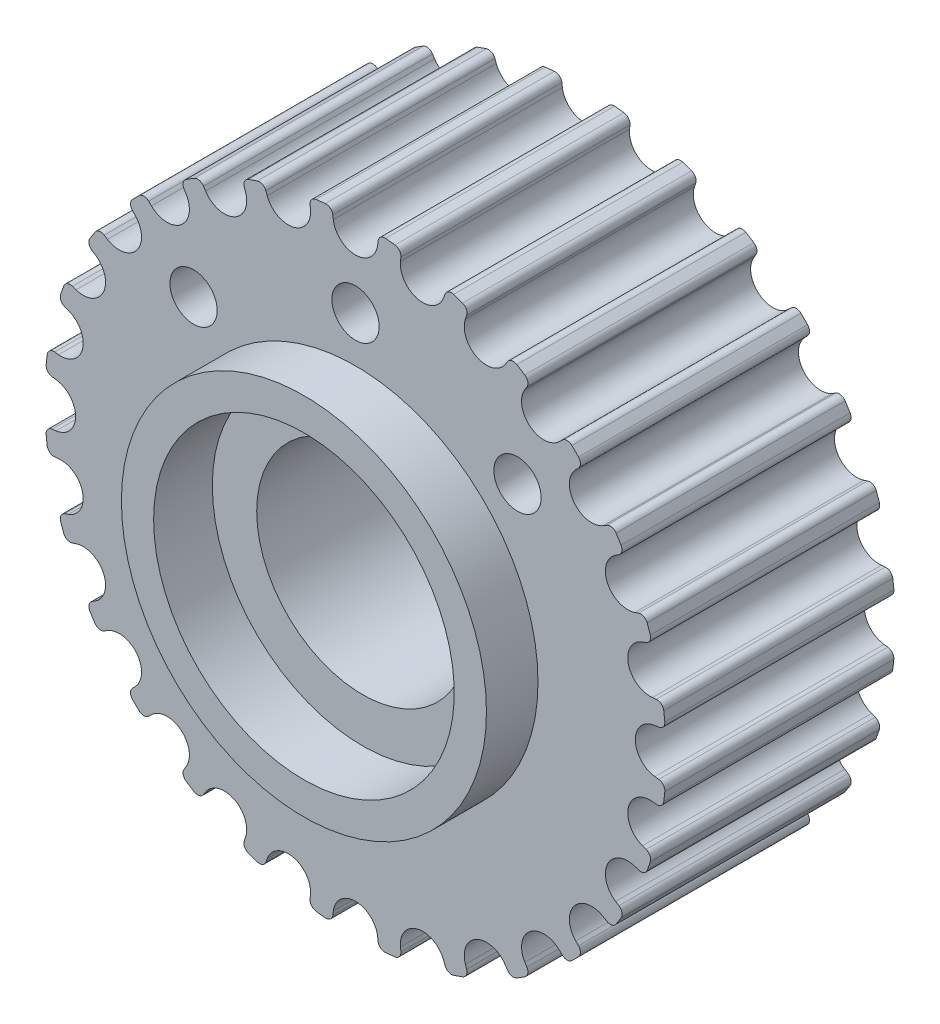
SolidWorks part; units mm, degrees
ref_plane "前视基准面" through (0, 0, 0) normal (0, 0, 1) x (1, 0, 0)
ref_plane "上视基准面" through (0, 0, 0) normal (0, 1, 0) x (1, 0, 0)
ref_plane "右视基准面" through (0, 0, 0) normal (1, 0, 0) x (0, 0, -1)
sketch "草图2" plane through (0, 0, 0) normal (0, 0, 1) x (1, 0, 0)
  line L36 (1.3319, 20.7804) -> (1.2989, 20.5118)
  line L37 (-1.7978, 20.5118) -> (-1.8308, 20.7804)
  line L38 (-3.4222, 20.6011) -> (-3.3946, 20.3319)
  line L39 (-6.4137, 19.6428) -> (-6.5056, 19.8973)
  line L40 (-8.0172, 19.3684) -> (-7.9303, 19.1121)
  line L41 (-10.7204, 17.7684) -> (-10.8667, 17.9962)
  line L42 (-12.2227, 17.1441) -> (-12.081, 16.9135)
  line L43 (-14.5021, 14.9827) -> (-14.6954, 15.1722)
  line L44 (-15.8278, 14.0398) -> (-15.6383, 13.8465)
  line L45 (-17.5691, 11.4254) -> (-17.7997, 11.5671)
  line L46 (-18.6517, 10.2111) -> (-18.424, 10.0648)
  line L47 (-19.7676, 7.2748) -> (-20.024, 7.3616)
  line L48 (-20.5529, 5.85) -> (-20.2983, 5.7581)
  line L49 (-20.9874, 2.739) -> (-21.2567, 2.7666)
  line L50 (-21.436, 1.1752) -> (-21.1673, 1.1423)
  line L51 (-21.1673, -1.9545) -> (-21.436, -1.9875)
  line L52 (-21.2567, -3.5789) -> (-20.9874, -3.5512)
  line L53 (-20.2983, -6.5703) -> (-20.5529, -6.6623)
  line L54 (-20.024, -8.1739) -> (-19.7676, -8.087)
  line L55 (-18.424, -10.8771) -> (-18.6517, -11.0234)
  line L56 (-17.7997, -12.3793) -> (-17.5691, -12.2376)
  line L57 (-15.6383, -14.6588) -> (-15.8278, -14.8521)
  line L58 (-14.6954, -15.9845) -> (-14.5021, -15.795)
  line L59 (-12.081, -17.7258) -> (-12.2227, -17.9564)
  line L60 (-10.8667, -18.8084) -> (-10.7204, -18.5807)
  line L61 (-7.9303, -19.9243) -> (-8.0172, -20.1806)
  line L62 (-6.5056, -20.7096) -> (-6.4137, -20.455)
  line L63 (-3.3946, -21.1441) -> (-3.4222, -21.4133)
  line L64 (-1.8308, -21.5926) -> (-1.7978, -21.324)
  line L65 (1.2989, -21.324) -> (1.3319, -21.5926)
  line L66 (2.9233, -21.4133) -> (2.8957, -21.1441)
  line L67 (5.9148, -20.455) -> (6.0067, -20.7096)
  line L68 (7.5183, -20.1806) -> (7.4314, -19.9243)
  line L69 (10.2215, -18.5807) -> (10.3678, -18.8084)
  line L70 (11.7238, -17.9564) -> (11.5821, -17.7258)
  line L71 (14.0032, -15.795) -> (14.1965, -15.9845)
  line L72 (15.3289, -14.8521) -> (15.1394, -14.6588)
  line L73 (17.0702, -12.2376) -> (17.3008, -12.3793)
  line L74 (18.1528, -11.0234) -> (17.9251, -10.8771)
  line L75 (19.2687, -8.087) -> (19.5251, -8.1739)
  line L76 (20.054, -6.6623) -> (19.7994, -6.5703)
  line L77 (20.4885, -3.5512) -> (20.7578, -3.5789)
  line L78 (20.9371, -1.9875) -> (20.6684, -1.9545)
  line L79 (20.6684, 1.1423) -> (20.9371, 1.1752)
  line L80 (20.7578, 2.7666) -> (20.4885, 2.739)
  line L81 (19.7994, 5.7581) -> (20.054, 5.85)
  line L82 (19.5251, 7.3616) -> (19.2687, 7.2748)
  line L83 (17.9251, 10.0648) -> (18.1528, 10.2111)
  line L84 (17.3008, 11.5671) -> (17.0702, 11.4254)
  line L85 (15.1394, 13.8465) -> (15.3289, 14.0398)
  line L86 (14.1965, 15.1722) -> (14.0032, 14.9827)
  line L87 (11.5821, 16.9135) -> (11.7238, 17.1441)
  line L88 (10.3678, 17.9962) -> (10.2215, 17.7684)
  line L89 (7.4314, 19.1121) -> (7.5183, 19.3684)
  line L90 (6.0067, 19.8973) -> (5.9148, 19.6428)
  line L91 (2.8957, 20.3319) -> (2.9233, 20.6011)
  circle A72 centre (-0.2458, -0.3677) radius 12 construction
  circle A73 centre (-0.2458, -0.3677) radius 10.5
  arc A74 (2.9233, 20.6011) -> (2.5067, 21.1262) centre (2.4458, 20.6501) ccw
  arc A75 (2.5067, 21.1262) -> (1.8549, 21.1996) centre (-0.2495, -0.4061) ccw
  arc A76 (1.8549, 21.1996) -> (1.3319, 20.7804) centre (1.8083, 20.7219) ccw
  arc A77 (-1.7978, 20.5118) -> (1.2989, 20.5118) centre (-0.2495, 20.7019) ccw
  arc A78 (-1.8308, 20.7804) -> (-2.3538, 21.1996) centre (-2.3072, 20.7219) ccw
  arc A79 (-2.3538, 21.1996) -> (-3.0056, 21.1262) centre (-0.2495, -0.4061) ccw
  arc A80 (-3.0056, 21.1262) -> (-3.4222, 20.6011) centre (-2.9447, 20.6501) ccw
  arc A81 (-6.4137, 19.6428) -> (-3.3946, 20.3319) centre (-4.9464, 20.1727) ccw
  arc A82 (-6.5056, 19.8973) -> (-7.1087, 20.1897) centre (-6.9571, 19.7343) ccw
  arc A83 (-7.1087, 20.1897) -> (-7.7279, 19.973) centre (-0.2495, -0.4061) ccw
  arc A84 (-7.7279, 19.973) -> (-8.0172, 19.3684) centre (-7.5626, 19.5224) ccw
  arc A85 (-10.7204, 17.7684) -> (-7.9303, 19.1121) centre (-9.4079, 18.6115) ccw
  arc A86 (-10.8667, 17.9962) -> (-11.5198, 18.147) centre (-11.2706, 17.7367) ccw
  arc A87 (-11.5198, 18.147) -> (-12.0752, 17.798) centre (-0.2495, -0.4061) ccw
  arc A88 (-12.0752, 17.798) -> (-12.2227, 17.1441) centre (-11.8137, 17.3954) ccw
  arc A89 (-14.5021, 14.9827) -> (-12.081, 16.9135) centre (-13.4101, 16.0968) ccw
  arc A90 (-14.6954, 15.1722) -> (-15.3656, 15.1739) centre (-15.0314, 14.8294) ccw
  arc A91 (-15.3656, 15.1739) -> (-15.8295, 14.7101) centre (-0.2495, -0.4061) ccw
  arc A92 (-15.8295, 14.7101) -> (-15.8278, 14.0398) centre (-15.485, 14.3758) ccw
  arc A93 (-17.5691, 11.4254) -> (-15.6383, 13.8465) centre (-16.7524, 12.7545) ccw
  arc A94 (-17.7997, 11.5671) -> (-18.4535, 11.4196) centre (-18.051, 11.1582) ccw
  arc A95 (-18.4535, 11.4196) -> (-18.8026, 10.8642) centre (-0.2495, -0.4061) ccw
  arc A96 (-18.8026, 10.8642) -> (-18.6517, 10.2111) centre (-18.3923, 10.615) ccw
  arc A97 (-19.7676, 7.2748) -> (-18.424, 10.0648) centre (-19.2671, 8.7523) ccw
  arc A98 (-20.024, 7.3616) -> (-20.6286, 7.0724) centre (-20.178, 6.907) ccw
  arc A99 (-20.6286, 7.0724) -> (-20.8453, 6.4532) centre (-0.2495, -0.4061) ccw
  arc A100 (-20.8453, 6.4532) -> (-20.5529, 5.85) centre (-20.3899, 6.3015) ccw
  arc A101 (-20.9874, 2.739) -> (-20.2983, 5.7581) centre (-20.8282, 4.2909) ccw
  arc A102 (-21.2567, 2.7666) -> (-21.7818, 2.3501) centre (-21.3057, 2.2891) ccw
  arc A103 (-21.7818, 2.3501) -> (-21.8552, 1.6982) centre (-0.2495, -0.4061) ccw
  arc A104 (-21.8552, 1.6982) -> (-21.436, 1.1752) centre (-21.3775, 1.6517) ccw
  arc A105 (-21.1673, -1.9545) -> (-21.1673, 1.1423) centre (-21.3575, -0.4061) ccw
  arc A106 (-21.436, -1.9875) -> (-21.8552, -2.5104) centre (-21.3775, -2.4639) ccw
  arc A107 (-21.8552, -2.5104) -> (-21.7818, -3.1623) centre (-0.2495, -0.4061) ccw
  arc A108 (-21.7818, -3.1623) -> (-21.2567, -3.5789) centre (-21.3057, -3.1014) ccw
  arc A109 (-20.2983, -6.5703) -> (-20.9874, -3.5512) centre (-20.8282, -5.1031) ccw
  arc A110 (-20.5529, -6.6623) -> (-20.8453, -7.2654) centre (-20.3899, -7.1137) ccw
  arc A111 (-20.8453, -7.2654) -> (-20.6286, -7.8846) centre (-0.2495, -0.4061) ccw
  arc A112 (-20.6286, -7.8846) -> (-20.024, -8.1739) centre (-20.178, -7.7192) ccw
  arc A113 (-18.424, -10.8771) -> (-19.7676, -8.087) centre (-19.2671, -9.5645) ccw
  arc A114 (-18.6517, -11.0234) -> (-18.8026, -11.6764) centre (-18.3923, -11.4272) ccw
  arc A115 (-18.8026, -11.6764) -> (-18.4535, -12.2319) centre (-0.2495, -0.4061) ccw
  arc A116 (-18.4535, -12.2319) -> (-17.7997, -12.3793) centre (-18.051, -11.9704) ccw
  arc A117 (-15.6383, -14.6588) -> (-17.5691, -12.2376) centre (-16.7524, -13.5667) ccw
  arc A118 (-15.8278, -14.8521) -> (-15.8295, -15.5223) centre (-15.485, -15.1881) ccw
  arc A119 (-15.8295, -15.5223) -> (-15.3656, -15.9862) centre (-0.2495, -0.4061) ccw
  arc A120 (-15.3656, -15.9862) -> (-14.6954, -15.9845) centre (-15.0314, -15.6417) ccw
  arc A121 (-12.081, -17.7258) -> (-14.5021, -15.795) centre (-13.4101, -16.909) ccw
  arc A122 (-12.2227, -17.9564) -> (-12.0752, -18.6102) centre (-11.8137, -18.2077) ccw
  arc A123 (-12.0752, -18.6102) -> (-11.5198, -18.9592) centre (-0.2495, -0.4061) ccw
  arc A124 (-11.5198, -18.9592) -> (-10.8667, -18.8084) centre (-11.2706, -18.549) ccw
  arc A125 (-7.9303, -19.9243) -> (-10.7204, -18.5807) centre (-9.4079, -19.4238) ccw
  arc A126 (-8.0172, -20.1806) -> (-7.7279, -20.7853) centre (-7.5626, -20.3347) ccw
  arc A127 (-7.7279, -20.7853) -> (-7.1087, -21.0019) centre (-0.2495, -0.4061) ccw
  arc A128 (-7.1087, -21.0019) -> (-6.5056, -20.7096) centre (-6.9571, -20.5465) ccw
  arc A129 (-3.3946, -21.1441) -> (-6.4137, -20.455) centre (-4.9464, -20.9849) ccw
  arc A130 (-3.4222, -21.4133) -> (-3.0056, -21.9384) centre (-2.9447, -21.4623) ccw
  arc A131 (-3.0056, -21.9384) -> (-2.3538, -22.0119) centre (-0.2495, -0.4061) ccw
  arc A132 (-2.3538, -22.0119) -> (-1.8308, -21.5926) centre (-2.3072, -21.5341) ccw
  arc A133 (1.2989, -21.324) -> (-1.7978, -21.324) centre (-0.2495, -21.5141) ccw
  arc A134 (1.3319, -21.5926) -> (1.8549, -22.0119) centre (1.8083, -21.5341) ccw
  arc A135 (1.8549, -22.0119) -> (2.5067, -21.9384) centre (-0.2495, -0.4061) ccw
  arc A136 (2.5067, -21.9384) -> (2.9233, -21.4133) centre (2.4458, -21.4623) ccw
  arc A137 (5.9148, -20.455) -> (2.8957, -21.1441) centre (4.4475, -20.9849) ccw
  arc A138 (6.0067, -20.7096) -> (6.6098, -21.0019) centre (6.4582, -20.5465) ccw
  arc A139 (6.6098, -21.0019) -> (7.229, -20.7853) centre (-0.2495, -0.4061) ccw
  arc A140 (7.229, -20.7853) -> (7.5183, -20.1806) centre (7.0637, -20.3347) ccw
  arc A141 (10.2215, -18.5807) -> (7.4314, -19.9243) centre (8.909, -19.4238) ccw
  arc A142 (10.3678, -18.8084) -> (11.0209, -18.9592) centre (10.7716, -18.549) ccw
  arc A143 (11.0209, -18.9592) -> (11.5763, -18.6102) centre (-0.2495, -0.4061) ccw
  arc A144 (11.5763, -18.6102) -> (11.7238, -17.9564) centre (11.3148, -18.2077) ccw
  arc A145 (14.0032, -15.795) -> (11.5821, -17.7258) centre (12.9112, -16.909) ccw
  arc A146 (14.1965, -15.9845) -> (14.8667, -15.9862) centre (14.5325, -15.6417) ccw
  arc A147 (14.8667, -15.9862) -> (15.3306, -15.5223) centre (-0.2495, -0.4061) ccw
  arc A148 (15.3306, -15.5223) -> (15.3289, -14.8521) centre (14.9861, -15.1881) ccw
  arc A149 (17.0702, -12.2376) -> (15.1394, -14.6588) centre (16.2534, -13.5667) ccw
  arc A150 (17.3008, -12.3793) -> (17.9546, -12.2319) centre (17.5521, -11.9704) ccw
  arc A151 (17.9546, -12.2319) -> (18.3036, -11.6764) centre (-0.2495, -0.4061) ccw
  arc A152 (18.3036, -11.6764) -> (18.1528, -11.0234) centre (17.8934, -11.4272) ccw
  arc A153 (19.2687, -8.087) -> (17.9251, -10.8771) centre (18.7682, -9.5645) ccw
  arc A154 (19.5251, -8.1739) -> (20.1297, -7.8846) centre (19.6791, -7.7192) ccw
  arc A155 (20.1297, -7.8846) -> (20.3464, -7.2654) centre (-0.2495, -0.4061) ccw
  arc A156 (20.3464, -7.2654) -> (20.054, -6.6623) centre (19.891, -7.1137) ccw
  arc A157 (20.4885, -3.5512) -> (19.7994, -6.5703) centre (20.3293, -5.1031) ccw
  arc A158 (20.7578, -3.5789) -> (21.2829, -3.1623) centre (20.8067, -3.1014) ccw
  arc A159 (21.2829, -3.1623) -> (21.3563, -2.5104) centre (-0.2495, -0.4061) ccw
  arc A160 (21.3563, -2.5104) -> (20.9371, -1.9875) centre (20.8786, -2.4639) ccw
  arc A161 (20.6684, 1.1423) -> (20.6684, -1.9545) centre (20.8585, -0.4061) ccw
  arc A162 (20.9371, 1.1752) -> (21.3563, 1.6982) centre (20.8786, 1.6517) ccw
  arc A163 (21.3563, 1.6982) -> (21.2829, 2.3501) centre (-0.2495, -0.4061) ccw
  arc A164 (21.2829, 2.3501) -> (20.7578, 2.7666) centre (20.8067, 2.2891) ccw
  arc A165 (19.7994, 5.7581) -> (20.4885, 2.739) centre (20.3293, 4.2909) ccw
  arc A166 (20.054, 5.85) -> (20.3464, 6.4532) centre (19.891, 6.3015) ccw
  arc A167 (20.3464, 6.4532) -> (20.1297, 7.0724) centre (-0.2495, -0.4061) ccw
  arc A168 (20.1297, 7.0724) -> (19.5251, 7.3616) centre (19.6791, 6.907) ccw
  arc A169 (17.9251, 10.0648) -> (19.2687, 7.2748) centre (18.7682, 8.7523) ccw
  arc A170 (18.1528, 10.2111) -> (18.3036, 10.8642) centre (17.8934, 10.615) ccw
  arc A171 (18.3036, 10.8642) -> (17.9546, 11.4196) centre (-0.2495, -0.4061) ccw
  arc A172 (17.9546, 11.4196) -> (17.3008, 11.5671) centre (17.5521, 11.1582) ccw
  arc A173 (15.1394, 13.8465) -> (17.0702, 11.4254) centre (16.2534, 12.7545) ccw
  arc A174 (15.3289, 14.0398) -> (15.3306, 14.7101) centre (14.9861, 14.3758) ccw
  arc A175 (15.3306, 14.7101) -> (14.8667, 15.1739) centre (-0.2495, -0.4061) ccw
  arc A176 (14.8667, 15.1739) -> (14.1965, 15.1722) centre (14.5325, 14.8294) ccw
  arc A177 (11.5821, 16.9135) -> (14.0032, 14.9827) centre (12.9112, 16.0968) ccw
  arc A178 (11.7238, 17.1441) -> (11.5763, 17.798) centre (11.3148, 17.3954) ccw
  arc A179 (11.5763, 17.798) -> (11.0209, 18.147) centre (-0.2495, -0.4061) ccw
  arc A180 (11.0209, 18.147) -> (10.3678, 17.9962) centre (10.7716, 17.7367) ccw
  arc A181 (7.4314, 19.1121) -> (10.2215, 17.7684) centre (8.909, 18.6115) ccw
  arc A182 (7.5183, 19.3684) -> (7.229, 19.973) centre (7.0637, 19.5224) ccw
  arc A183 (7.229, 19.973) -> (6.6098, 20.1897) centre (-0.2495, -0.4061) ccw
  arc A184 (6.6098, 20.1897) -> (6.0067, 19.8973) centre (6.4582, 19.7343) ccw
  arc A185 (2.8957, 20.3319) -> (5.9148, 19.6428) centre (4.4475, 20.1727) ccw
  dimension "D1" = 21
extrude "凸台-拉伸1" add sketch "草图2" along normal blind 16
move or copy body "实体-移动/复制1" bodies to move or copy 106 copy no translate (-21.7751, 0, 0) parameters "D1"=21.7751, "D2"=0, "D3"=0
sketch "草图12" plane through (0, 0, 16) normal (0, 0, 1) x (1, 0, 0)
  circle A0 centre (-22.0209, -0.3677) radius 10.5 construction
  circle A1 centre (-22.0209, -0.3677) radius 10.5
  circle A2 centre (-22.0246, -0.3096) radius 11.5
  circle A3 centre (-22.0246, -0.3096) radius 13
  circle A4 centre (-22.0209, -0.3677) radius 16
  point P7 (-6.0209, -0.3677)
  point P10 (-10.7072, -11.6815)
  point P11 (-22.0209, -16.3677)
  point P12 (-33.3346, -11.6815)
  point P13 (-38.0209, -0.3677)
  point P14 (-33.3346, 10.946)
  point P15 (-22.0209, 15.6323)
  point P16 (-10.7072, 10.946)
  point P17 (-22.0209, -0.3677)
  dimension "D1" = 23
  dimension "D2" = 26
  dimension "D3" = 32
  dimension "D4" = 8
extrude "凸台-拉伸2" add sketch "草图12" along normal blind 4 and the other way blind 18 contours A3 A2
sketch "草图14" plane through (0, 0, 16) normal (0, 0, 1) x (1, 0, 0)
  circle A0 centre (-22.0209, -0.3677) radius 10.5 construction
  circle A1 centre (-22.0246, -0.3096) radius 11.5
  circle A2 centre (-22.0246, -0.3096) radius 11.5
  circle A3 centre (-22.0209, -0.3677) radius 10.5
  dimension "D1" = 0
extrude "切除-拉伸1" cut sketch "草图14" against normal blind 1.1
sketch "草图15" plane through (0, 0, 16) normal (0, 0, 1) x (1, 0, 0)
  circle A0 centre (-22.0209, -0.3677) radius 16 construction
  circle A1 centre (-22.0209, -0.3677) radius 16 construction
  circle A2 centre (-22.0209, 15.6323) radius 4.05
  circle A3 centre (-10.7072, 10.946) radius 4.05
  circle A4 centre (-6.0209, -0.3677) radius 4.05 [skipped]
  circle A8 centre (-38.0209, -0.3677) radius 4.05 [skipped]
  circle A9 centre (-33.3346, 10.946) radius 4.05
  circle A10 centre (-10.7072, -11.6815) radius 4.05 [skipped]
  circle A11 centre (-33.3346, -11.6815) radius 4.05 [skipped]
  circle A12 centre (-22.0209, -16.3677) radius 4.05 [skipped]
  point P0 (-33.3346, -11.6815)
  point P2 (-22.0209, -16.3677)
  point P4 (-10.7072, -11.6815)
  point P6 (-10.7072, 10.946)
  point P8 (-22.0209, 15.6323)
  point P10 (-33.3346, 10.946)
  point P34 (-22.0209, -0.3677)
  dimension "D1" = 8.1
  dimension "D2" = 8
sketch "草图16" plane through (0, 0, 0) normal (0, 0, -1) x (-1, 0, 0)
  circle A0 centre (22.0209, -0.3677) radius 10.5 construction
  circle A1 centre (22.0246, -0.3096) radius 11.5
  circle A2 centre (22.0246, -0.3096) radius 11.5
  circle A3 centre (22.0209, -0.3677) radius 10.5
  dimension "D1" = 0
sketch "草图18" plane through (0, 0, 0) normal (0, 0, -1) x (-1, 0, 0)
  line L0 (22.0209, -0.3677) -> (22.0209, 21.2599) construction
  line L1 (22.0209, -0.3677) -> (3.1451, 18.5081) construction
  line L2 (22.0209, -0.3677) -> (38.7709, 16.3822) construction
  circle A0 centre (22.0209, -0.3677) radius 16 construction
  circle A1 centre (10.7072, 10.946) radius 1.65
  circle A3 centre (22.0209, 15.6323) radius 1.65
  circle A4 centre (33.3346, 10.946) radius 1.65
  circle A5 centre (22.0209, -0.3677) radius 12.9417 construction
  point P14 (33.3346, 10.946)
  dimension "D1" = 32
  dimension "D3" = 3.3
  dimension "D4" = 3.3
  dimension "D6" = 3.3
  dimension "D2" = 45
  dimension "D5" = 45
extrude "切除-拉伸5" cut sketch "草图16" against normal blind 1.1
sketch "草图20" plane through (0, 0, 20) normal (0, 0, 1) x (1, 0, 0)
  circle A0 centre (-22.0246, -0.3096) radius 11.9673
extrude "凸台-拉伸3" add sketch "草图20" against normal up to surface (22 mm away) up to face at (-10.5246, -0.3096, -2)
sketch "草图21" plane through (0, 0, -2) normal (0, 0, -1) x (-1, 0, 0)
  circle A0 centre (22.0246, -0.3096) radius 13
extrude "凸台-拉伸4" add sketch "草图21" along normal blind 1
sketch "草图22" plane through (0, 0, -3) normal (0, 0, -1) x (-1, 0, 0)
  circle A0 centre (22.0246, -0.3096) radius 11.5
  circle A1 centre (22.0246, -0.3096) radius 8.5
  dimension "D1" = 23
  dimension "D2" = 17
extrude "切除-拉伸6" cut sketch "草图22" against normal blind 4.1
sketch "草图23" plane through (0, 0, -3) normal (0, 0, -1) x (-1, 0, 0)
  circle A0 centre (22.0246, -0.3096) radius 8.5
extrude "切除-拉伸7" cut sketch "草图23" against normal blind 33.1
sketch "草图24" plane through (0, 0, 20) normal (0, 0, 1) x (1, 0, 0)
  circle A0 centre (-22.0246, -0.3096) radius 11.5
  dimension "D1" = 23
extrude "切除-拉伸8" cut sketch "草图24" against normal blind 4.1
sketch "草图25" plane through (0, 0, -3) normal (0, 0, -1) x (-1, 0, 0)
  circle A0 centre (22.0246, -0.3096) radius 14.3512
extrude "切除-拉伸9" cut sketch "草图25" against normal blind 35
sketch "草图26" plane through (0, 0, 0) normal (0, 0, -1) x (-1, 0, 0)
  circle A0 centre (22.0246, -0.3096) radius 14.8679
extrude "凸台-拉伸5" add sketch "草图26" against normal up to surface (16 mm away) up to face at (-7.6733, -0.3096, 16)
sketch "草图27" plane through (0, 0, 0) normal (0, 0, -1) x (-1, 0, 0)
  circle A0 centre (22.0246, -0.3096) radius 7.4
  dimension "D1" = 14.8
extrude "切除-拉伸10" cut sketch "草图27" against normal blind 27
sketch "草图30" plane through (0, 0, 0) normal (0, 0, -1) x (-1, 0, 0)
  circle A0 centre (22.0246, -0.3096) radius 10.5
  circle A1 centre (22.0246, -0.3096) radius 12.75
  dimension "D1" = 21
  dimension "D2" = 25.5
extrude "凸台-拉伸6" add sketch "草图30" along normal blind 3.6 contours A1 | A0
sketch "草图31" plane through (0, 0, 0) normal (0, 0, -1) x (-1, 0, 0)
  circle A1 centre (22.0246, -0.3096) radius 10.5
extrude "切除-拉伸13" cut sketch "草图31" against normal blind 0.5
ref_plane "基准面2" through (0, 0, 8) normal (0, 0, -1) x (-1, 0, 0)
mirror "镜向2" about plane through (0, 0, 8) normal (0, 0, -1) of "切除-拉伸13", "凸台-拉伸6"
extrude "切除-拉伸15" cut sketch "草图18" against normal blind 25
